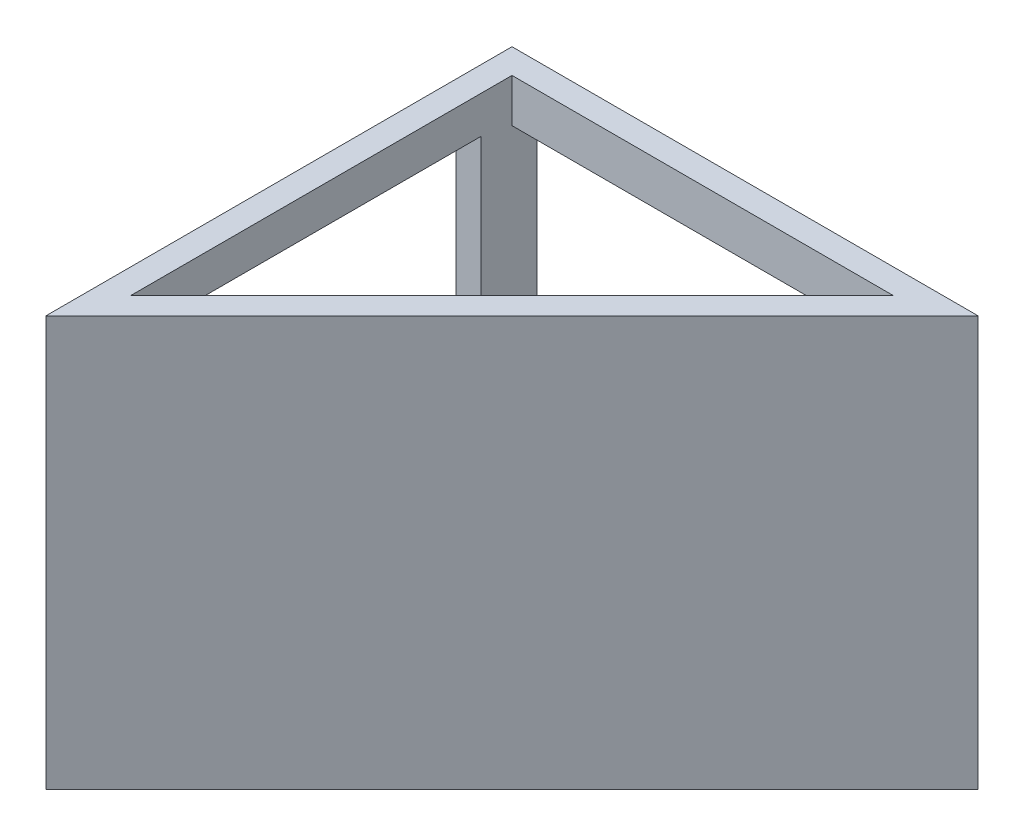
SolidWorks part; units mm, degrees
ref_plane "Front Plane" through (0, 0, 0) normal (0, 0, 1) x (1, 0, 0)
ref_plane "Top Plane" through (0, 0, 0) normal (0, 1, 0) x (1, 0, 0)
ref_plane "Right Plane" through (0, 0, 0) normal (1, 0, 0) x (0, 0, -1)
sketch "Sketch1" plane through (0, 0, 0) normal (0, 1, 0) x (1, 0, 0)
  line L0 (0, 0) -> (37.5, 0)
  line L1 (0, 0) -> (0, -37.5)
  line L2 (0, -37.5) -> (37.5, 0)
  line L3 (2, -2) -> (32.6716, -2)
  line L4 (2, -32.6716) -> (32.6716, -2)
  line L5 (2, -2) -> (2, -32.6716)
  dimension "D1" = 37.5
  dimension "D2" = 2
extrude "Boss-Extrude1" add sketch "Sketch1" along normal blind 33
sketch "Sketch2" plane through (0, 0, 0) normal (0, -1, 0) x (1, 0, 0)
  line L0 (2, 32.6716) -> (32.6716, 2) construction
  line L1 (32.6716, 2) -> (2, 2) construction
  line L2 (2, 2) -> (2, 32.6716) construction
  line L3 (2, 32.6716) -> (32.6716, 2)
  line L4 (32.6716, 2) -> (2, 2)
  line L5 (2, 2) -> (2, 32.6716)
extrude "Boss-Extrude2" add sketch "Sketch2" against normal blind 2
sketch "Sketch3" plane through (0, 0, 0) normal (0, 0, -1) x (-1, 0, 0)
  line L0 (-37.5, 0) -> (0, 0) construction
  line L1 (-31, 29.5) -> (-2, 29.5)
  line L2 (-31, 29.5) -> (-31, 3)
  line L3 (-31, 3) -> (-2, 3)
  line L4 (-2, 29.5) -> (-2, 3)
  line L5 (-37.5, 33) -> (-37.5, 0) construction
  dimension "D1" = 26.5
  dimension "D2" = 29
  dimension "D3" = 3
  dimension "D4" = 6.5
extrude "Cut-Extrude1" cut sketch "Sketch3" against normal blind 2
sketch "Sketch4" plane through (0, 0, 0) normal (-1, 0, 0) x (0, 0, 1)
  line L0 (0, 0) -> (37.5, 0) construction
  line L1 (4.5, 30) -> (33, 30)
  line L2 (4.5, 30) -> (4.5, 5)
  line L3 (4.5, 5) -> (33, 5)
  line L4 (33, 30) -> (33, 5)
  line L5 (0, 33) -> (0, 0) construction
  dimension "D1" = 25
  dimension "D2" = 28.5
  dimension "D3" = 5
  dimension "D4" = 4.5
extrude "Cut-Extrude2" cut sketch "Sketch4" against normal blind 2
